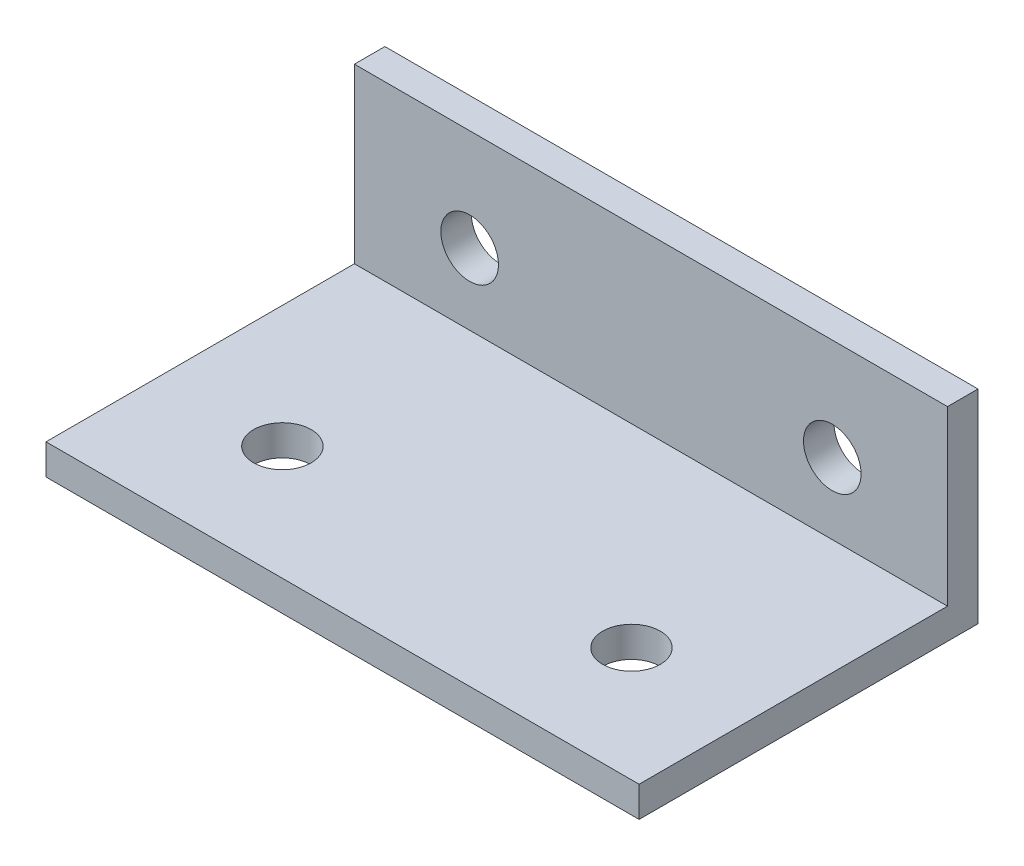
SolidWorks part; units mm, degrees
material "3.0205 (EN-AW 1200)"
ref_plane "Plan de face" through (0, 0, 0) normal (0, 0, 1) x (1, 0, 0)
ref_plane "Plan de dessus" through (0, 0, 0) normal (0, 1, 0) x (1, 0, 0)
ref_plane "Plan de droite" through (0, 0, 0) normal (1, 0, 0) x (0, 0, -1)
sketch "Esquisse1" plane through (0, 0, 0) normal (0, 1, 0) x (1, 0, 0)
  line L1 (-17.5, 10) -> (17.5, 10)
  line L2 (-17.5, 10) -> (-17.5, -10)
  line L3 (-17.5, -10) -> (17.5, -10)
  line L4 (17.5, 10) -> (17.5, -10)
  line L5 (-17.5, 10) -> (17.5, -10) construction
  line L6 (-17.5, -10) -> (17.5, 10) construction
  point P0 (0, 0)
  dimension "D1" = 35
  dimension "D2" = 20
extrude "Boss.-Extru.1" add sketch "Esquisse1" along normal blind 1.8
sketch "Esquisse2" plane through (0, 1.8, 0) normal (0, 1, 0) x (1, 0, 0)
  line L0 (17.5, -10) -> (17.5, 10) construction
  line L1 (-17.5, 10) -> (17.5, 10)
  line L2 (-17.5, 10) -> (-17.5, 8.2)
  line L3 (-17.5, 8.2) -> (17.5, 8.2)
  line L4 (17.5, 10) -> (17.5, 8.2)
  dimension "D1" = 1.8
extrude "Boss.-Extru.2" add sketch "Esquisse2" along normal blind 10.2
sketch "Esquisse5" plane through (0, 0, -8.2) normal (0, 0, 1) x (1, 0, 0)
  line L0 (-17.5, 12) -> (-17.5, 1.8) construction
  line L1 (-17.5, 0) -> (17.5, 0) construction
  point P0 (-10.7, 6)
  point P1 (10.7, 6)
  dimension "D1" = 6.8
  dimension "D2" = 6
  dimension "D3" = 6
  dimension "D4" = 28.2
hole_wizard "Dégagement M31" positions "Esquisse7" profile "Esquisse6" hole size "M3" standard "ISO" end condition through all
sketch "Esquisse7" plane through (0, 0, -8.2) normal (0, 0, 1) x (1, 0, 0)
  point P0 (-10.7, 6)
  point P3 (10.7, 6)
sketch "Esquisse6" plane through (-10.7, 6, -8.2) normal (1, 0, 0) x (0, -1, 0)
  line L0 (0, 0) -> (0, 1.8)
  line L1 (0, 1.8) -> (1.7, 1.8)
  line L2 (1.7, 1.8) -> (1.7, 0)
  line L5 (1.7, 0) -> (0, 0)
  line L11 (0, -6.35) -> (0, 107.95) construction
  dimension "Diamètre du perçage jusqu'au prochain" = 3.4
  dimension "Profondeur du perçage jusqu'au prochain" = 1.8
sketch "Esquisse8" plane through (0, 1.8, 0) normal (0, 1, 0) x (1, 0, 0)
  line L0 (-17.5, -10) -> (17.5, -10) construction
  line L1 (-17.5, 8.2) -> (-17.5, -10) construction
  point P0 (-10.3, -3.25)
  point P1 (10.3, -3.25)
  dimension "D1" = 6.75
  dimension "D2" = 6.75
  dimension "D3" = 7.2
  dimension "D4" = 27.8
hole_wizard "Dégagement M32" positions "Esquisse10" profile "Esquisse9" hole size "M3" standard "ISO" end condition through all
sketch "Esquisse10" plane through (0, 1.8, 0) normal (0, 1, 0) x (1, 0, 0)
  point P0 (-10.3, -3.25)
  point P3 (10.3, -3.25)
sketch "Esquisse9" plane through (-10.3, 1.8, 3.25) normal (1, 0, 0) x (0, 0, 1)
  line L0 (0, 0) -> (0, 1.8)
  line L1 (0, 1.8) -> (1.7, 1.8)
  line L2 (1.7, 1.8) -> (1.7, 0)
  line L5 (1.7, 0) -> (0, 0)
  line L11 (0, -6.35) -> (0, 107.95) construction
  dimension "Diamètre du perçage jusqu'au prochain" = 3.4
  dimension "Profondeur du perçage jusqu'au prochain" = 1.8
